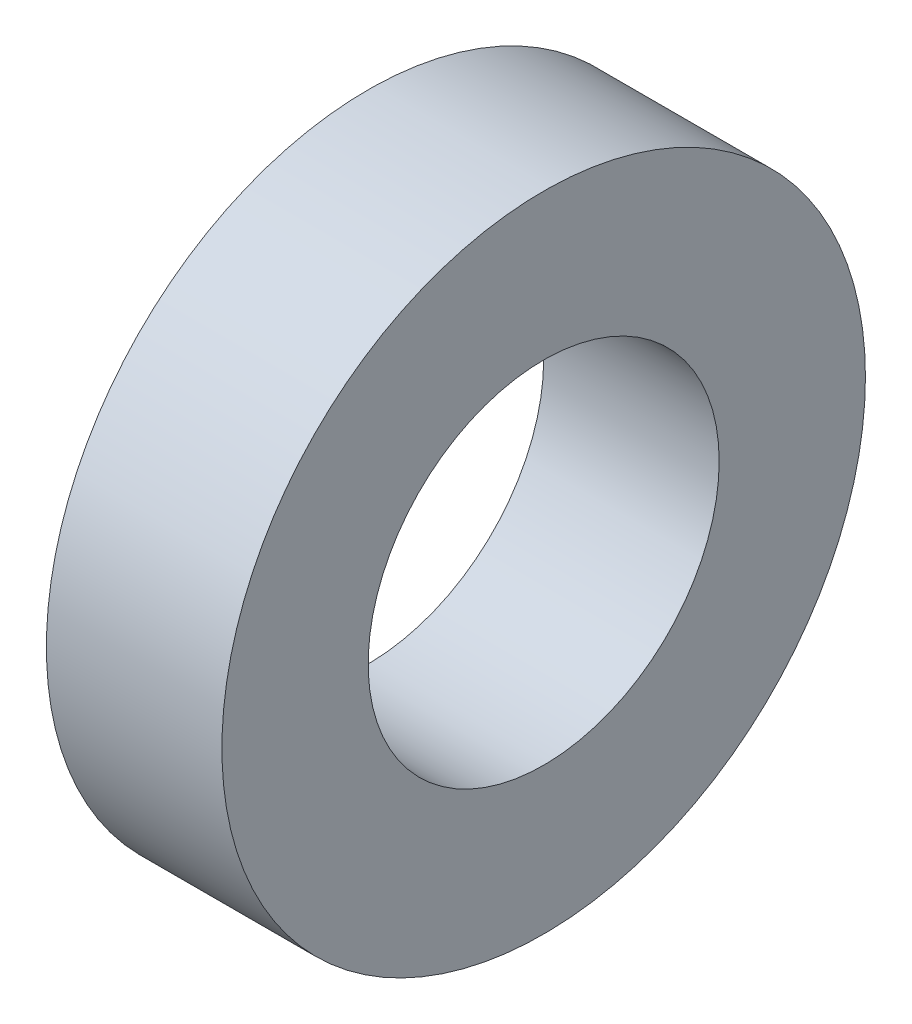
SolidWorks part; units mm, degrees
ref_plane "前视基准面" through (0, 0, 0) normal (0, 0, 1) x (1, 0, 0)
ref_plane "上视基准面" through (0, 0, 0) normal (0, 1, 0) x (1, 0, 0)
ref_plane "右视基准面" through (0, 0, 0) normal (1, 0, 0) x (0, 0, -1)
sketch "草图1" plane through (0, 0, 0) normal (1, 0, 0) x (0, 0, -1)
  circle A0 centre (0, 0) radius 3
  circle A1 centre (0, 0) radius 5.5
extrude "凸台-拉伸1" add sketch "草图1" along normal blind 3
